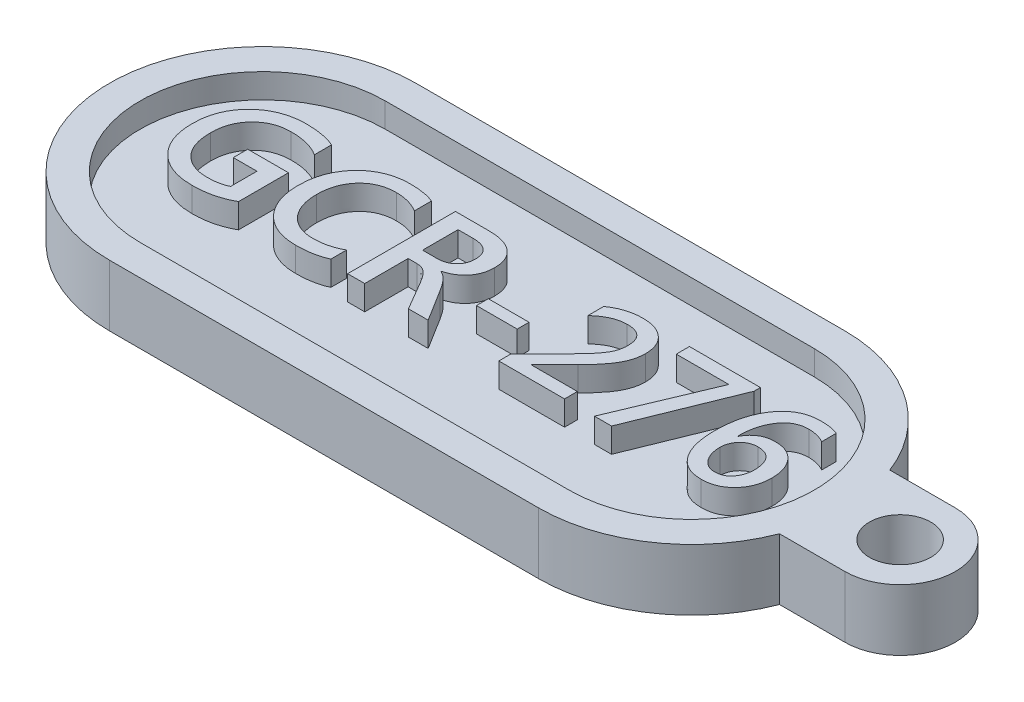
SolidWorks part; units mm, degrees
ref_plane "前基準面" through (0, 0, 0) normal (0, 0, 1) x (1, 0, 0)
ref_plane "上基準面" through (0, 0, 0) normal (0, 1, 0) x (1, 0, 0)
ref_plane "右基準面" through (0, 0, 0) normal (1, 0, 0) x (0, 0, -1)
sketch "草圖1" plane through (0, 0, 0) normal (0, 1, 0) x (1, 0, 0)
  line L0 (0, 0) -> (35, 0) construction
  line L1 (0, 12.5) -> (35, 12.5)
  line L2 (0, -12.5) -> (35, -12.5)
  line L3 (47.5, 0) -> (47.5, 23.3491) construction
  line L4 (-12.5, 0) -> (-12.5, 27.7516) construction
  arc A0 (0, 12.5) -> (0, -12.5) centre (0, 0) ccw
  arc A1 (35, -12.5) -> (35, 12.5) centre (35, 0) ccw
  point P3 (17.5, 0)
  dimension "D1" = 12.5
  dimension "D2" = 60
extrude "填料-伸長1" add sketch "草圖1" along normal blind 5
sketch "草圖2" plane through (0, 5, 0) normal (0, 1, 0) x (1, 0, 0)
  line L4 (0, -10) -> (35, -10)
  line L5 (35, 10) -> (0, 10)
  line L6 (0, -10) -> (35, -10)
  line L7 (35, 10) -> (0, 10)
  arc A4 (0, 10) -> (0, -10) centre (0, 0) ccw
  arc A5 (35, -10) -> (35, 10) centre (35, 0) ccw
  arc A6 (0, 10) -> (0, -10) centre (0, 0) ccw
  arc A7 (35, -10) -> (35, 10) centre (35, 0) ccw
  dimension "D1" = 2.5
extrude "除料-伸長1" cut sketch "草圖2" against normal blind 2
sketch "草圖3" plane through (0, 3, 0) normal (0, 1, 0) x (1, 0, 0)
  text T0 "GCR-276" font "微軟正黑體" height in points 28
extrude "填料-伸長3" add sketch "草圖3" along normal blind 2
sketch "草圖4" plane through (0, 5, 0) normal (0, 1, 0) x (1, 0, 0)
  line L0 (51.1805, 0) -> (52, 0) construction
  line L1 (52, 4.5) -> (46.6619, 4.5)
  line L2 (52, -4.5) -> (46.6619, -4.5)
  arc A1 (52, 4.5) -> (52, -4.5) centre (52, 0) cw
  arc A4 (35, -12.5) -> (35, 12.5) centre (35, 0) ccw construction
  arc A5 (46.6619, -4.5) -> (46.6619, 4.5) centre (35, 0) ccw
  circle A6 centre (52, 0) radius 2.5
  dimension "D1" = 4.5
  dimension "D3" = 5
  dimension "D2" = 52
extrude "填料-伸長4" add sketch "草圖4" against normal up to surface (5 mm away) up to face at (17.5, 0, 0)
